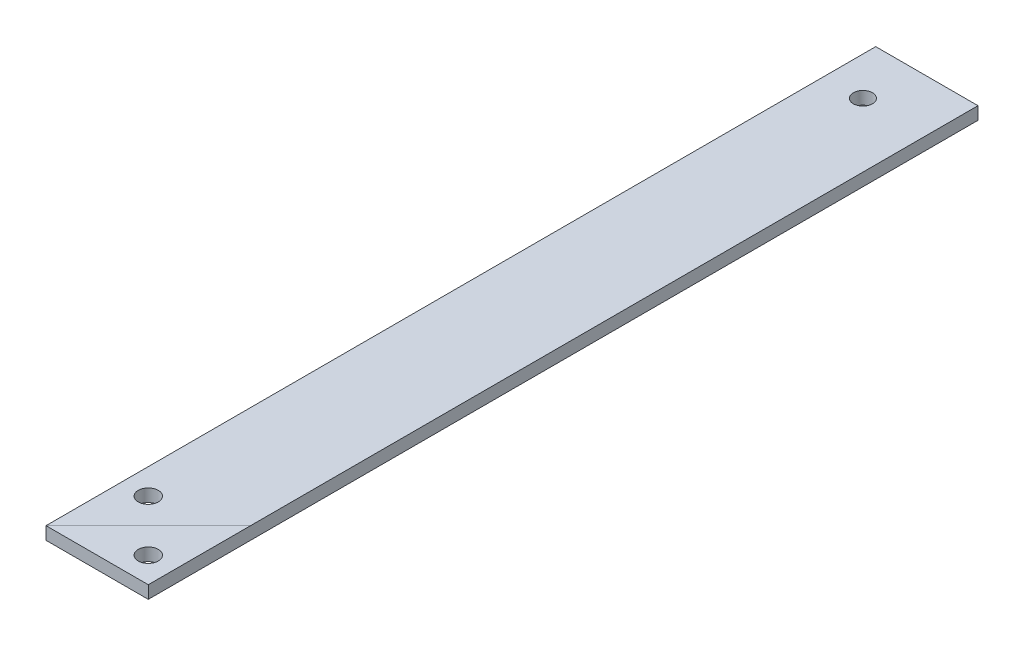
SolidWorks part; units mm, degrees
ref_plane "Alzado" through (0, 0, 0) normal (0, 0, 1) x (1, 0, 0)
ref_plane "Planta" through (0, 0, 0) normal (0, 1, 0) x (1, 0, 0)
ref_plane "Vista lateral" through (0, 0, 0) normal (1, 0, 0) x (0, 0, -1)
sketch "Croquis1" plane through (0, 0, 0) normal (0, 1, 0) x (1, 0, 0)
  line L1 (25.4, -151.87) -> (-25.4, -151.87)
  line L2 (25.4, -151.87) -> (25.4, 151.87)
  line L3 (25.4, 151.87) -> (-25.4, 151.87)
  line L4 (-25.4, -151.87) -> (-25.4, 151.87)
  line L5 (25.4, -151.87) -> (-25.4, 151.87) construction
  line L6 (25.4, 151.87) -> (-25.4, -151.87) construction
  point P0 (0, 0)
  dimension "D1" = 50.8
  dimension "D2" = 303.74
extrude "Saliente-Extruir1" add sketch "Croquis1" along normal blind 6.31
sketch "Croquis2" plane through (0, 6.31, 0) normal (0, 1, 0) x (1, 0, 0)
  line L0 (-25.4, -151.87) -> (-25.4, -145.56)
  line L1 (-25.4, 151.87) -> (-25.4, -151.87) construction
  line L2 (-25.4, -145.56) -> (25.4, -145.56)
  line L3 (25.4, -145.56) -> (25.4, -151.87)
  line L4 (25.4, -151.87) -> (-25.4, -151.87)
  dimension "D1" = 50.8
  dimension "D2" = 6.31
sketch "Croquis3" plane through (0, 0, 151.87) normal (0, 0, 1) x (1, 0, 0)
  line L1 (-25.4, 0) -> (25.4, 0)
  line L2 (-25.4, 0) -> (-25.4, 6.31)
  line L3 (-25.4, 6.31) -> (25.4, 6.31)
  line L4 (25.4, 0) -> (25.4, 6.31)
  line L5 (-25.4, 0) -> (25.4, 6.31) construction
  line L6 (-25.4, 6.31) -> (25.4, 0) construction
  point P0 (0, 3.155)
sketch3d "Croquis3D1"
  line L0 (0, 3.155, 151.87) -> (0, 3.155, 234.8257)
  line L1 (-25.4, 0, 151.87) -> (25.4, 6.31, 151.87) construction
  line L2 (0, 3.155, 234.8257) -> (306, 3.155, 234.8257)
  dimension "D1" = 306
  dimension "D2" = 82.9557
sweep "Barrer1" add profiles "Croquis3" path "Croquis3D1"
sketch "Croquis4" plane through (0, 0, 0) normal (0, -1, 0) x (1, 0, 0)
  line L0 (0, 234.8257) -> (306, 234.8257) construction
  line L1 (299.69, 209.4257) -> (306, 209.4257)
  line L2 (299.69, 209.4257) -> (299.69, 260.2257)
  line L3 (299.69, 260.2257) -> (306, 260.2257)
  line L4 (306, 209.4257) -> (306, 260.2257)
  line L5 (299.69, 209.4257) -> (306, 260.2257) construction
  line L6 (299.69, 260.2257) -> (306, 209.4257) construction
  point P0 (302.845, 234.8257)
  dimension "D1" = 6.31
extrude "Saliente-Extruir2" add sketch "Croquis4" along normal blind 60
sketch "Croquis6" plane through (0, 6.31, 0) normal (0, 1, 0) x (1, 0, 0)
  line L0 (25.4, 151.87) -> (19.09, 151.87)
  line L1 (25.4, 151.87) -> (-25.4, 151.87) construction
  line L2 (19.09, 151.87) -> (19.09, 101.07)
  line L3 (19.09, 101.07) -> (25.4, 101.07)
  line L4 (25.4, -209.4257) -> (25.4, 151.87) construction
  line L5 (25.4, 101.07) -> (25.4, 151.87)
  dimension "D1" = 50.8
  dimension "D2" = 6.31
extrude "Saliente-Extruir3" add sketch "Croquis6" along normal blind 50
sketch "Croquis7" plane through (19.09, 0, 0) normal (-1, 0, 0) x (0, 0, 1)
  line L0 (-111.12, 22.65) -> (-111.12, 29) construction
  line L1 (-149.47, 28.9985) -> (-143.8224, 29.344) construction
  circle A0 centre (-111.12, 29) radius 6.35 construction
  circle A1 centre (-143.12, 29) radius 6.35 construction
  circle A2 centre (-111.12, 29) radius 6.35
  circle A3 centre (-143.8224, 29.344) radius 5.6582
sketch "Croquis8" plane through (19.09, 0, 0) normal (-1, 0, 0) x (0, 0, 1)
  line L0 (-143.12, 29) -> (-138.0327, 25.1998) construction
  line L1 (-111.12, 29) -> (-113.6531, 23.1771) construction
  circle A0 centre (-143.12, 29) radius 6.35 construction
  circle A1 centre (-111.12, 29) radius 6.35 construction
  circle A2 centre (-111.12, 29) radius 6.35
  circle A3 centre (-143.12, 29) radius 6.35
extrude "Cortar-Extruir2" cut sketch "Croquis8" against normal blind 10
sketch "Croquis9" plane through (306, 0, 0) normal (1, 0, 0) x (0, 0, -1)
  line L0 (-260.2257, -60) -> (-260.2257, -9.2)
  line L1 (-260.2257, 6.31) -> (-260.2257, -60) construction
  line L2 (-260.2257, -9.2) -> (-253.9157, -9.2)
  line L3 (-253.9157, -9.2) -> (-253.9157, -60)
  line L4 (-209.4257, -60) -> (-260.2257, -60) construction
  line L5 (-260.2257, -60) -> (-253.9157, -60)
  dimension "D1" = 50.8
  dimension "D2" = 6.31
extrude "Saliente-Extruir4" add sketch "Croquis9" along normal blind 50.8
sketch "Croquis10" plane through (0, 6.31, 0) normal (0, 1, 0) x (1, 0, 0)
  line L0 (-25.4, 151.87) -> (25.4, 151.87)
  line L1 (25.4, 151.87) -> (25.4, -209.4257)
  line L2 (25.4, -209.4257) -> (25.4, -260.2257)
  line L3 (-25.4, -260.2257) -> (306, -260.2257) construction
  line L4 (25.4, -260.2257) -> (-25.4, -260.2257)
  line L5 (-25.4, -260.2257) -> (-25.4, 151.87)
sketch "Croquis11" plane through (19.09, 0, 0) normal (-1, 0, 0) x (0, 0, 1)
  line L0 (-101.07, 6.31) -> (-151.87, 6.31)
  line L1 (-151.87, 6.31) -> (-151.87, 56.31)
  line L2 (-151.87, 56.31) -> (-101.07, 56.31)
  line L3 (-101.07, 56.31) -> (-101.07, 6.31)
extrude "Cortar-Extruir3" cut sketch "Croquis11" against normal blind 10
sketch "Croquis12" plane through (0, 6.31, 0) normal (0, 1, 0) x (1, 0, 0)
  line L0 (25.4, -209.4257) -> (25.4, -260.2257)
  line L1 (25.4, -260.2257) -> (306, -260.2257)
  line L2 (306, -260.2257) -> (366.9296, -260.2257)
  line L3 (366.9296, -260.2257) -> (366.9296, -209.4257)
  line L4 (366.9296, -209.4257) -> (25.4, -209.4257)
extrude "Cortar-Extruir4" cut sketch "Croquis12" against normal blind 97.8
sketch "Croquis13" plane through (0, 6.31, 0) normal (0, 1, 0) x (1, 0, 0)
  line L0 (-6.36, 126.47) -> (-6.36, 128.4901) construction
  circle A0 centre (-6.36, 126.47) radius 4.7625
  dimension "D1" = 9.525
extrude "Cortar-Extruir5" cut sketch "Croquis13" against normal blind 9.525
sketch "Croquis14" plane through (0, 6.31, 0) normal (0, 1, 0) x (1, 0, 0)
  line L0 (-8.7998, -225.2543) -> (-12.7, -222.1257) construction
  line L1 (-12.7, -222.1257) -> (12.7, -247.5257) construction
  circle A0 centre (12.7, -247.5257) radius 5
  circle A1 centre (-12.7, -222.1257) radius 5
  dimension "D1" = 10
  dimension "D2" = 10
extrude "Cortar-Extruir6" cut sketch "Croquis14" against normal blind 9.525
